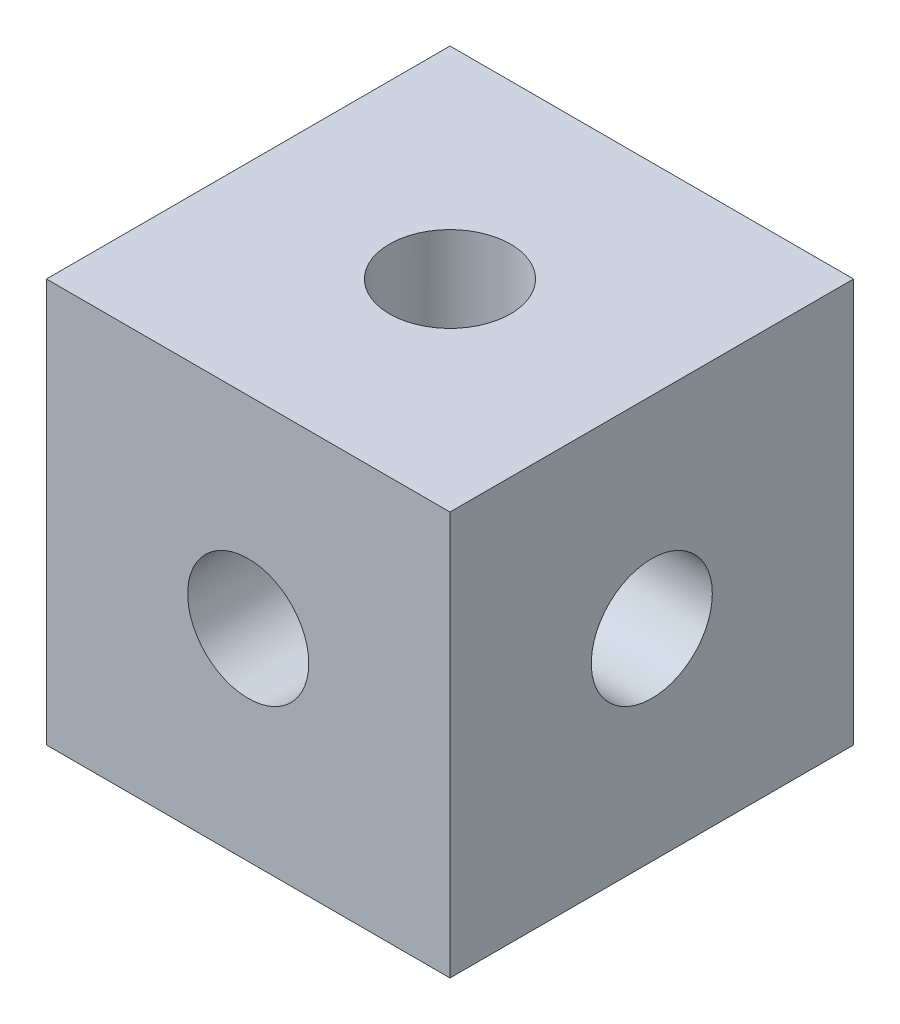
SolidWorks part; units mm, degrees
material "201 退火不锈钢 (SS)"
ref_plane "前视基准面" through (0, 0, 0) normal (0, 0, 1) x (1, 0, 0)
ref_plane "上视基准面" through (0, 0, 0) normal (0, 1, 0) x (1, 0, 0)
ref_plane "右视基准面" through (0, 0, 0) normal (1, 0, 0) x (0, 0, -1)
sketch "草图1" plane through (0, 0, 0) normal (0, 1, 0) x (1, 0, 0)
  line L1 (-5, -5) -> (5, -5)
  line L2 (-5, -5) -> (-5, 5)
  line L3 (-5, 5) -> (5, 5)
  line L4 (5, -5) -> (5, 5)
  line L5 (-5, -5) -> (5, 5) construction
  line L6 (-5, 5) -> (5, -5) construction
  circle A0 centre (0, 0) radius 1.5
  point P0 (0, 0)
  dimension "D3" = 3
  dimension "D1" = 10
  dimension "D2" = 10
extrude "凸台-拉伸1" add sketch "草图1" along normal blind 10
sketch "草图2" plane through (5, 0, 0) normal (1, 0, 0) x (0, 0, -1)
  line L0 (-5, 10) -> (-5, 0) construction
  circle A0 centre (0, 5) radius 1.5
  point P7 (-5, 5)
  dimension "D1" = 3
extrude "切除-拉伸1" cut sketch "草图2" against normal through all
sketch "草图3" plane through (0, 0, 5) normal (0, 0, 1) x (1, 0, 0)
  line L0 (-5, 10) -> (-5, 0) construction
  circle A0 centre (0, 5) radius 1.5
  point P7 (-5, 5)
  dimension "D1" = 3
extrude "切除-拉伸2" cut sketch "草图3" against normal through all
